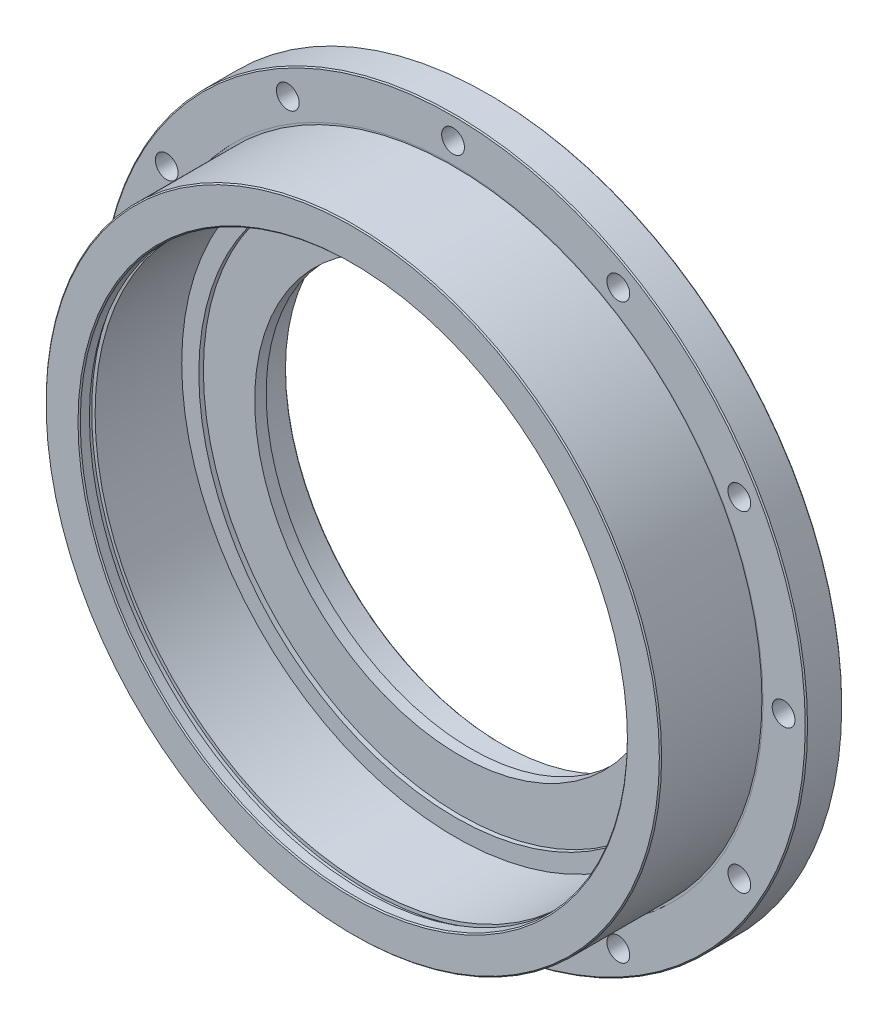
SolidWorks part; units mm, degrees
ref_plane "前视基准面" through (0, 0, 0) normal (0, 0, 1) x (1, 0, 0)
ref_plane "上视基准面" through (0, 0, 0) normal (0, 1, 0) x (1, 0, 0)
ref_plane "右视基准面" through (0, 0, 0) normal (1, 0, 0) x (0, 0, -1)
sketch "草图1" plane through (0, 0, 0) normal (0, 0, 1) x (1, 0, 0)
  circle A0 centre (0, 0) radius 155
  dimension "D1" = 310
extrude "拉伸1" add sketch "草图1" along normal blind 20
sketch "草图2" plane through (0, 0, 20) normal (0, 0, 1) x (1, 0, 0)
  circle A0 centre (0, 0) radius 135
extrude "拉伸2" add sketch "草图2" along normal blind 40
sketch "草图3" plane through (0, 0, 0) normal (0, 0, -1) x (-1, 0, 0)
  circle A0 centre (0, 0) radius 120
extrude "切除-拉伸1" cut sketch "草图3" against normal through all
sketch "草图4" plane through (0, 0, 0) normal (0, 0, -1) x (-1, 0, 0)
  circle A0 centre (0, 0) radius 120
  circle A1 centre (0, 0) radius 112.5
  dimension "D1" = 225
extrude "拉伸3" add sketch "草图4" against normal blind 15
ref_plane "基准面1" through (0, 0, 53) normal (0, 0, 1) x (1, 0, 0)
sketch "草图5" plane through (0, 0, 53) normal (0, 0, 1) x (1, 0, 0)
  circle A0 centre (0, 0) radius 120
  circle A1 centre (0, 0) radius 121.5
  dimension "D1" = 243
extrude "切除-拉伸2" cut sketch "草图5" along normal blind 2.5
sketch "草图7" plane through (0, 0, 20) normal (0, 0, 1) x (1, 0, 0)
  circle A0 centre (72.5, 125.5737) radius 5
  circle A1 centre (0, 145) radius 5
  circle A2 centre (125.5737, 72.5) radius 5
  circle A3 centre (145, 0) radius 5
  circle A4 centre (125.5737, -72.5) radius 5
  circle A5 centre (72.5, -125.5737) radius 5
  circle A6 centre (0, -145) radius 5
  circle A7 centre (-72.5, -125.5737) radius 5
  circle A8 centre (-125.5737, -72.5) radius 5
  circle A9 centre (-145, 0) radius 5
  circle A10 centre (-125.5737, 72.5) radius 5
  circle A11 centre (-72.5, 125.5737) radius 5
  dimension "D1" = 10
extrude "切除-拉伸3" cut sketch "草图7" against normal blind 25
sketch "草图9" plane through (0, 0, 0) normal (0, 0, -1) x (-1, 0, 0)
  circle A0 centre (0, 0) radius 120
  dimension "D1" = 240
extrude "切除-拉伸4" cut sketch "草图9" against normal blind 13
sketch "草图10" plane through (0, 0, 13) normal (0, 0, -1) x (-1, 0, 0)
  circle A0 centre (0, 0) radius 120
  circle A1 centre (0, 0) radius 95
extrude "拉伸4" add sketch "草图10" along normal blind 19
sketch "草图12" plane through (0, 0, 13) normal (0, 0, 1) x (1, 0, 0)
  circle A0 centre (0, 0) radius 95
  circle A1 centre (0, 0) radius 90
  dimension "D1" = 180
extrude "拉伸5" add sketch "草图12" against normal blind 5
sketch "草图13" plane through (0, 0, 20) normal (0, 0, 1) x (1, 0, 0)
  circle A0 centre (0, 0) radius 155
  circle A1 centre (0, 0) radius 135
extrude "切除-拉伸5" cut sketch "草图13" against normal blind 4
chamfer "倒角1" distance 0.5 angle 45 6 edges at (-120, 0, -6) (-95, 0, -6) (-120, 0, 60) (135, 0, 60) (155, 0, 0) (155, 0, 16)
sketch "草图14" plane through (0, 0, 0) normal (0, 1, 0) x (1, 0, 0)
  line L1 (-154.5, -16) -> (154.5, -16) construction
  line L2 (-135, -16) -> (135, -16) construction
  line L7 (-135, -16) -> (-136, -16)
  line L8 (-135, -16) -> (-135, -15.5)
  line L9 (-135, -15.5) -> (-136, -15.5)
  line L10 (-136, -16) -> (-136, -15.5)
  dimension "D1" = 0.5
  dimension "D2" = 1
ref_axis "基准轴1" through (0, 0, 8) along (0, 0, -1)
revolve "切除-旋转1" cut sketch "草图14" angle 360 about axis through (0, 0, 8) along (0, 0, -1)
